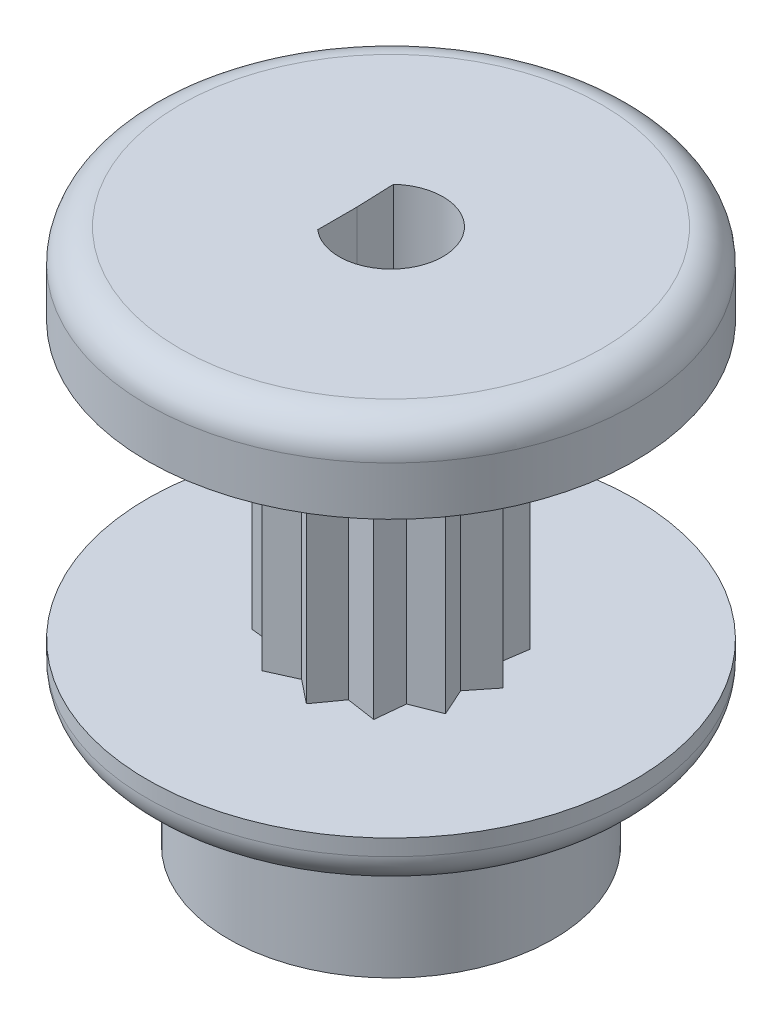
SolidWorks part; units mm, degrees
ref_plane "Plan de face" through (0, 0, 0) normal (0, 0, 1) x (1, 0, 0)
ref_plane "Plan de dessus" through (0, 0, 0) normal (0, 1, 0) x (1, 0, 0)
ref_plane "Plan de droite" through (0, 0, 0) normal (1, 0, 0) x (0, 0, -1)
sketch "Esquisse1" plane through (0, 0, 0) normal (0, 1, 0) x (1, 0, 0)
  line L31 (2.409, 1.876) -> (1.488, 1.9682)
  line L32 (2.409, 1.876) -> (2.2727, 0.9605)
  line L33 (3.0242, 0.4202) -> (2.2727, 0.9605)
  line L34 (3.0242, 0.4202) -> (2.4485, -0.3046)
  line L35 (2.8291, -1.1482) -> (2.4485, -0.3046)
  line L36 (2.8291, -1.1482) -> (1.9682, -1.488)
  line L37 (1.876, -2.409) -> (1.9682, -1.488)
  line L38 (1.876, -2.409) -> (0.9605, -2.2727)
  line L39 (0.4202, -3.0242) -> (0.9605, -2.2727)
  line L40 (0.4202, -3.0242) -> (-0.3046, -2.4485)
  line L41 (-1.1482, -2.8291) -> (-0.3046, -2.4485)
  line L42 (-1.1482, -2.8291) -> (-1.488, -1.9682)
  line L43 (-2.409, -1.876) -> (-1.488, -1.9682)
  line L44 (-2.409, -1.876) -> (-2.2727, -0.9605)
  line L45 (-3.0242, -0.4202) -> (-2.2727, -0.9605)
  line L46 (-3.0242, -0.4202) -> (-2.4485, 0.3046)
  line L47 (-2.8291, 1.1482) -> (-2.4485, 0.3046)
  line L48 (-2.8291, 1.1482) -> (-1.9682, 1.488)
  line L49 (-1.876, 2.409) -> (-1.9682, 1.488)
  line L50 (-1.876, 2.409) -> (-0.9605, 2.2727)
  line L51 (-0.4202, 3.0242) -> (-0.9605, 2.2727)
  line L52 (-0.4202, 3.0242) -> (0.3046, 2.4485)
  line L53 (1.1482, 2.8291) -> (0.3046, 2.4485)
  line L54 (1.1482, 2.8291) -> (1.488, 1.9682)
  point P65 (0, 0)
  dimension "D1" = 12
extrude "Boss.-Extru.2" add sketch "Esquisse1" along normal blind 8.5
sketch "Esquisse2" plane through (0, 8.5, 0) normal (0, 1, 0) x (1, 0, 0)
  circle A0 centre (0, 0) radius 7.5
extrude "Boss.-Extru.3" add sketch "Esquisse2" along normal blind 2.5
sketch "Esquisse3" plane through (0, 0, 0) normal (0, -1, 0) x (1, 0, 0)
  circle A0 centre (0, 0) radius 7.5
extrude "Boss.-Extru.4" add sketch "Esquisse3" along normal blind 1.5
sketch "Esquisse4" plane through (0, -1.5, 0) normal (0, -1, 0) x (1, 0, 0)
  circle A0 centre (0, 0) radius 5
extrude "Boss.-Extru.5" add sketch "Esquisse4" along normal blind 4
sketch "Esquisse6" plane through (0, -5.5, 0) normal (0, -1, 0) x (1, 0, 0)
  circle A0 centre (0, 0) radius 3
extrude "Enlèv. mat.-Extru.2" cut sketch "Esquisse6" against normal blind 0.1
fillet "Congé4" radius 1 2 edges at (0, -1.5, -7.5) (0, 11, 7.5)
sketch "Esquisse7" plane through (0, -5.4, 0) normal (0, -1, 0) x (1, 0, 0)
  line L0 (1.6, 0) -> (-1.0483, 0) construction
  line L1 (-1.0483, 0) -> (-1.0924, -1.169)
  line L2 (-1.0483, 0) -> (-1.0483, 1.2088)
  arc A0 (-1.0924, -1.169) -> (-1.0483, 1.2088) centre (0, 0) ccw
extrude "Enlèv. mat.-Extru.3" cut sketch "Esquisse7" against normal through all
